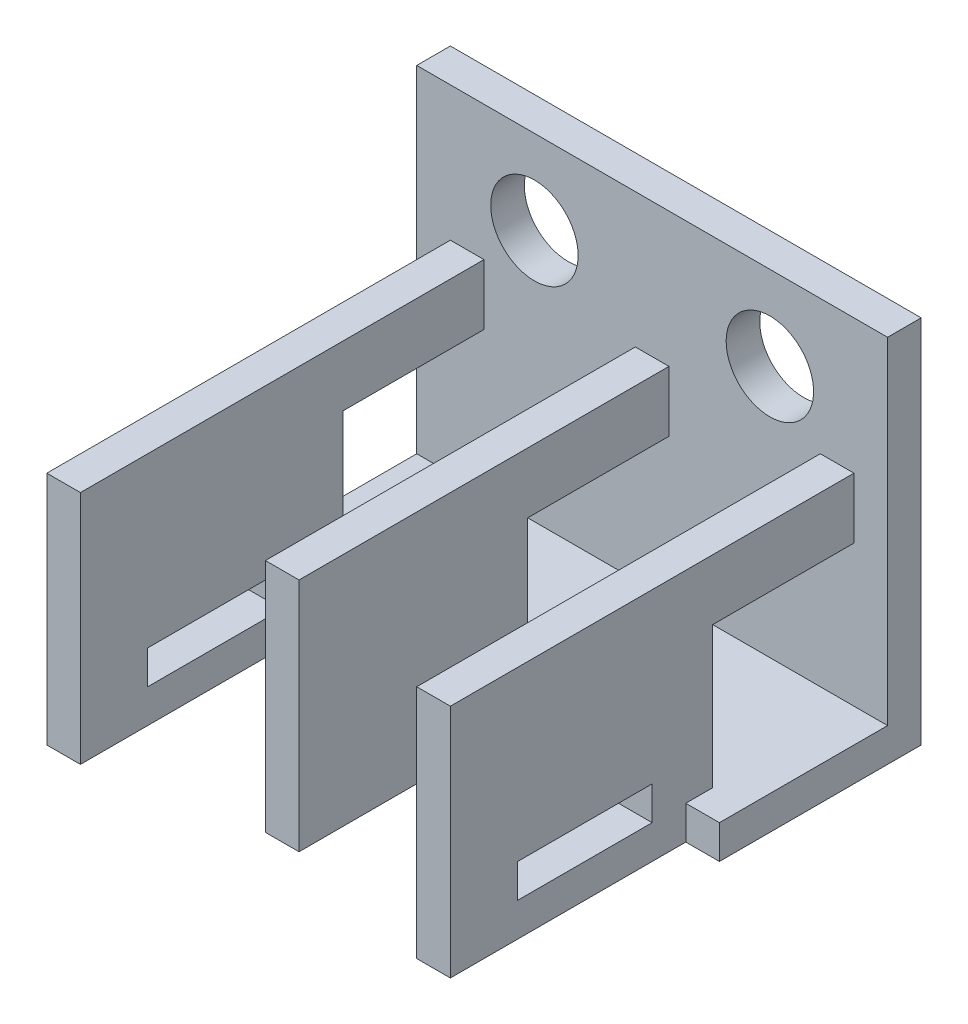
SolidWorks part; units mm, degrees
material "CA"
ref_plane "Front Plane" through (0, 0, 0) normal (0, 0, 1) x (1, 0, 0)
ref_plane "Top Plane" through (0, 0, 0) normal (0, 1, 0) x (1, 0, 0)
ref_plane "Right Plane" through (0, 0, 0) normal (1, 0, 0) x (0, 0, -1)
sketch "Sketch1" plane through (0, 0, 0) normal (0, 0, 1) x (1, 0, 0)
  line L1 (0, 0) -> (-70, 0)
  line L2 (0, 0) -> (0, 50)
  line L3 (0, 50) -> (-70, 50)
  line L4 (-70, 0) -> (-70, 50)
  dimension "D1" = 70
  dimension "D2" = 50
extrude "Boss-Extrude1" add sketch "Sketch1" along normal blind 5
sketch "Sketch2" plane through (0, 0, 5) normal (0, 0, 1) x (1, 0, 0)
  line L0 (-70, 0) -> (0, 0) construction
  line L1 (-65, 0) -> (-60, 0)
  line L2 (-65, 0) -> (-65, 30)
  line L3 (-65, 30) -> (-60, 30)
  line L4 (-60, 0) -> (-60, 30)
  line L5 (-70, 50) -> (-70, 0) construction
  line L6 (-37.5, 0) -> (-32.5, 0)
  line L7 (-37.5, 0) -> (-37.5, 30)
  line L8 (-37.5, 30) -> (-32.5, 30)
  line L9 (-32.5, 0) -> (-32.5, 30)
  line L10 (-5, 0) -> (-10, 0)
  line L11 (-5, 0) -> (-5, 30)
  line L12 (-5, 30) -> (-10, 30)
  line L13 (-10, 0) -> (-10, 30)
  line L14 (0, 0) -> (0, 50) construction
  point P18 (-35, 30)
  dimension "D1" = 5
  dimension "D2" = 5
  dimension "D3" = 5
  dimension "D4" = 5
  dimension "D5" = 5
  dimension "D6" = 35
  dimension "D7" = 30
  dimension "D8" = 30
  dimension "D9" = 30
extrude "Boss-Extrude2" add sketch "Sketch2" along normal blind 25
sketch "Sketch3" plane through (-5, 0, 0) normal (1, 0, 0) x (0, 0, -1)
  line L1 (-5, 0) -> (-26, 0)
  line L2 (-5, 0) -> (-5, 21)
  line L3 (-5, 21) -> (-26, 21)
  line L4 (-26, 0) -> (-26, 21)
  dimension "D1" = 21
  dimension "D2" = 21
extrude "Cut-Extrude1" cut sketch "Sketch3" against normal blind 5
sketch "Sketch4" plane through (-32.5, 0, 0) normal (1, 0, 0) x (0, 0, -1)
  line L1 (-5, 0) -> (-26, 0)
  line L2 (-5, 0) -> (-5, 21)
  line L3 (-5, 21) -> (-26, 21)
  line L4 (-26, 0) -> (-26, 21)
  dimension "D1" = 21
  dimension "D2" = 21
extrude "Cut-Extrude2" cut sketch "Sketch4" against normal blind 5
sketch "Sketch5" plane through (-60, 0, 0) normal (1, 0, 0) x (0, 0, -1)
  line L1 (-5, 0) -> (-26, 0)
  line L2 (-5, 0) -> (-5, 21)
  line L3 (-5, 21) -> (-26, 21)
  line L4 (-26, 0) -> (-26, 21)
  dimension "D1" = 21
  dimension "D2" = 21
extrude "Cut-Extrude3" cut sketch "Sketch5" against normal blind 5
sketch "Sketch6" plane through (0, 0, 0) normal (0, -1, 0) x (1, 0, 0)
  line L1 (0, 0) -> (-70, 0)
  line L2 (0, 0) -> (0, 30)
  line L3 (0, 30) -> (-70, 30)
  line L4 (-70, 0) -> (-70, 30)
  dimension "D1" = 30
  dimension "D2" = 70
extrude "Boss-Extrude3" add sketch "Sketch6" along normal blind 5
sketch "Sketch7" plane through (0, 0, 30) normal (0, 0, 1) x (1, 0, 0)
  line L0 (0, -5) -> (-70, -5) construction
  line L1 (-32.5, 30) -> (-37.5, 30)
  line L2 (-32.5, 30) -> (-32.5, -5)
  line L3 (-32.5, -5) -> (-37.5, -5)
  line L4 (-37.5, 30) -> (-37.5, -5)
  line L6 (-5, 30) -> (-10, 30)
  line L7 (-5, 30) -> (-5, -5)
  line L8 (-5, -5) -> (-10, -5)
  line L9 (-10, 30) -> (-10, -5)
  line L10 (-60, 30) -> (-65, 30)
  line L11 (-60, 30) -> (-60, -5)
  line L12 (-60, -5) -> (-65, -5)
  line L13 (-65, 30) -> (-65, -5)
extrude "Boss-Extrude4" add sketch "Sketch7" along normal blind 35
sketch "Sketch8" plane through (0, 0, 0) normal (0, 0, -1) x (-1, 0, 0)
  line L0 (0, 50) -> (70, 50) construction
  line L1 (0, -5) -> (0, 50) construction
  line L2 (70, 50) -> (70, -5) construction
  circle A0 centre (17.5, 37.5) radius 6.5
  circle A1 centre (52.5, 37.5) radius 6.5
  dimension "D1" = 13
  dimension "D2" = 13
  dimension "D4" = 17.5
  dimension "D5" = 12.5
  dimension "D6" = 17.5
  dimension "D3" = 12.5
extrude "Cut-Extrude4" cut sketch "Sketch8" against normal blind 5
sketch "Sketch9" plane through (0, 0, 65) normal (0, 0, 1) x (1, 0, 0)
  line L1 (-32.5, -5) -> (-37.5, -5)
  line L2 (-32.5, -5) -> (-32.5, 30)
  line L3 (-32.5, 30) -> (-37.5, 30)
  line L4 (-37.5, -5) -> (-37.5, 30)
extrude "Cut-Extrude5" cut sketch "Sketch9" against normal blind 5
sketch "Sketch10" plane through (-5, 0, 0) normal (1, 0, 0) x (0, 0, -1)
  line L0 (-65, -5) -> (-30, -5) construction
  line L1 (-55, 0) -> (-35, 0)
  line L2 (-55, 0) -> (-55, 5)
  line L3 (-55, 5) -> (-35, 5)
  line L4 (-35, 0) -> (-35, 5)
  line L5 (-65, -5) -> (-65, 30) construction
  dimension "D1" = 5
  dimension "D2" = 20
  dimension "D3" = 5
  dimension "D4" = 10
extrude "Cut-Extrude6" cut sketch "Sketch10" against normal blind 5
sketch "Sketch11" plane through (-65, 0, 0) normal (-1, 0, 0) x (0, 0, 1)
  line L0 (65, -5) -> (30, -5) construction
  line L1 (35, 0) -> (55, 0)
  line L2 (35, 0) -> (35, 5)
  line L3 (35, 5) -> (55, 5)
  line L4 (55, 0) -> (55, 5)
  line L5 (65, 30) -> (65, -5) construction
  dimension "D1" = 20
  dimension "D2" = 5
  dimension "D3" = 5
  dimension "D4" = 10
extrude "Cut-Extrude7" cut sketch "Sketch11" against normal blind 5
